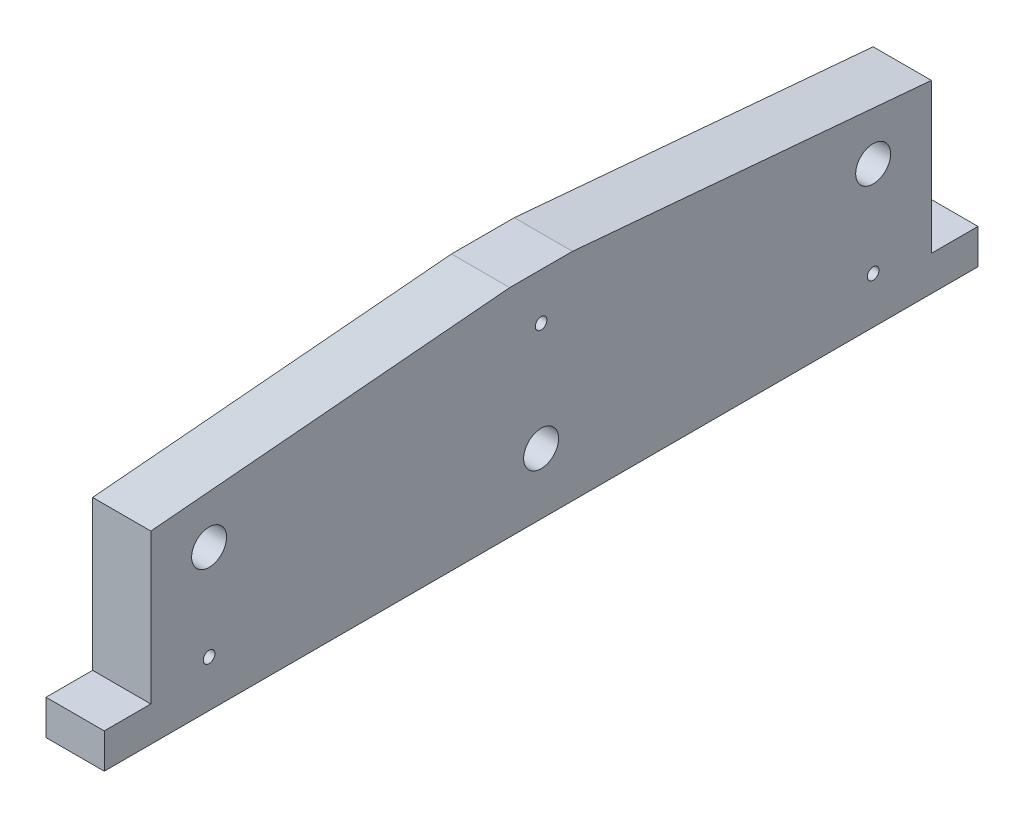
SolidWorks part; units mm, degrees
ref_plane "Plano frontal" through (0, 0, 0) normal (0, 0, 1) x (1, 0, 0)
ref_plane "Plano superior" through (0, 0, 0) normal (0, 1, 0) x (1, 0, 0)
ref_plane "Plano direito" through (0, 0, 0) normal (1, 0, 0) x (0, 0, -1)
sketch "Esboço2" plane through (0, 0, 0) normal (1, 0, 0) x (0, 0, -1)
  line L0 (67, -31.4899) -> (75, -31.4899)
  line L4 (-67, -5.7807) -> (-67, -31.4899)
  line L5 (-5.3908, -0.3906) -> (-67, -5.7807)
  line L6 (-5.3908, -0.3906) -> (0, -0.3906)
  line L8 (0, 0) -> (0, -35.5446) construction
  line L10 (5.3908, -0.3906) -> (0, -0.3906)
  line L11 (5.3908, -0.3906) -> (67, -5.7807)
  line L12 (67, -5.7807) -> (67, -31.4899)
  line L19 (-75, -37.4899) -> (75, -37.4899)
  line L20 (-75, -37.4899) -> (-75, -31.4899)
  line L21 (-75, -31.4899) -> (-67, -31.4899)
  line L22 (75, -37.4899) -> (75, -31.4899)
  dimension "D1" = 6
  dimension "D2" = 134
  dimension "D3" = 8
  dimension "D6" = 8
extrude "Ressalto-extrusão2" add sketch "Esboço2" along normal blind 10
sketch "Sketch1" plane through (0, 0, 0) normal (-1, 0, 0) x (0, 0, 1)
  line L0 (0, 0) -> (0, -37.4899) construction
  line L1 (75, -37.4899) -> (-75, -37.4899) construction
  line L2 (-67, -31.4899) -> (-67, -5.7807) construction
  line L3 (-5.3908, -0.3906) -> (5.3908, -0.3906) construction
  circle A0 centre (-57, -29.4899) radius 1
  circle A1 centre (57, -29.4899) radius 1
  circle A2 centre (0, -8.3906) radius 1
  circle A3 centre (0, -27.0028) radius 3
  circle A4 centre (-57, -13.1788) radius 3
  circle A5 centre (57, -13.1788) radius 3
  dimension "D1" = 10
  dimension "D2" = 8
  dimension "D3" = 8
  dimension "D4" = 6
extrude "Cut-Extrude1" cut sketch "Sketch1" against normal through all
